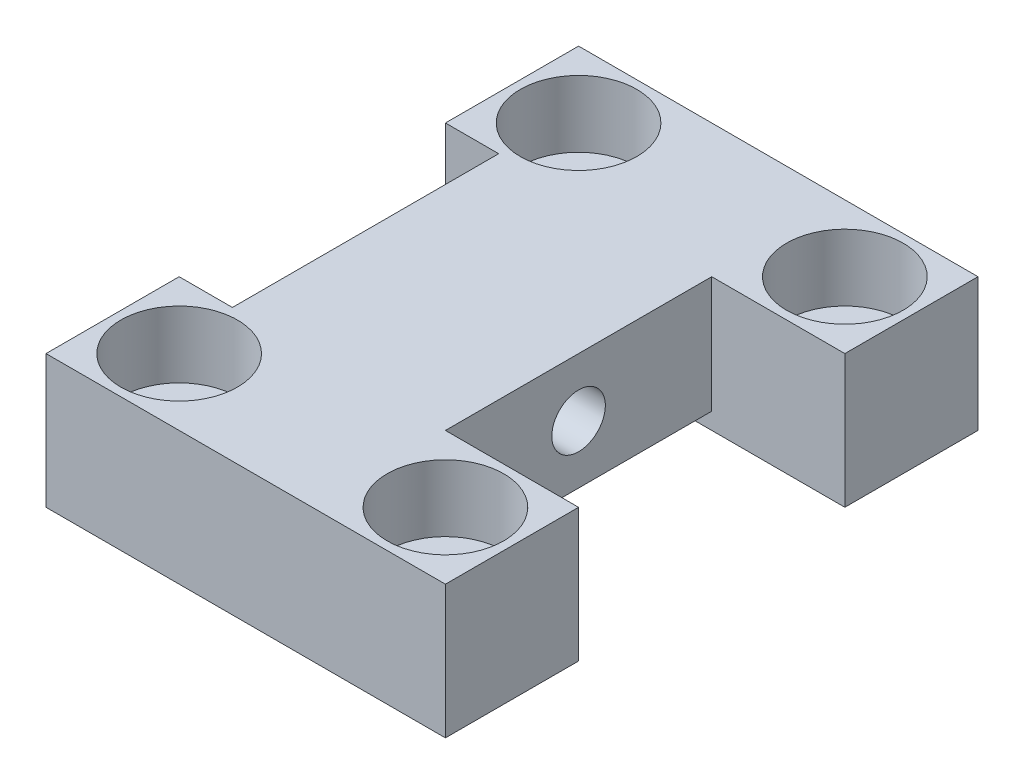
SolidWorks part; units mm, degrees
ref_plane "Front Plane" through (0, 0, 0) normal (0, 0, 1) x (1, 0, 0)
ref_plane "Top Plane" through (0, 0, 0) normal (0, 1, 0) x (1, 0, 0)
ref_plane "Right Plane" through (0, 0, 0) normal (1, 0, 0) x (0, 0, -1)
sketch "Sketch1" plane through (0, 0, 0) normal (0, 1, 0) x (1, 0, 0)
  line L0 (-19.05, 25.4) -> (19.05, -25.4) construction
  line L1 (-19.05, 25.4) -> (19.05, 25.4)
  line L2 (-19.05, 25.4) -> (-19.05, -25.4)
  line L3 (-19.05, -25.4) -> (19.05, -25.4)
  line L4 (19.05, 25.4) -> (19.05, -25.4)
  dimension "D1" = 50.8
  dimension "D2" = 38.1
extrude "Extrude1" add sketch "Sketch1" along normal blind 12.7
hole_wizard "CBORE for 1/4 Socket Head Cap Screw1" positions "Sketch10" profile "Sketch9" counterbore size "1/4" standard "Ansi Inch" end condition through all
sketch "Sketch10" plane through (0, 12.7, 0) normal (0, 1, 0) x (-1, 0, 0)
  line L1 (-12.7, -19.05) -> (12.7, -19.05)
  line L2 (-12.7, -19.05) -> (-12.7, 19.05)
  line L3 (-12.7, 19.05) -> (12.7, 19.05)
  line L4 (12.7, -19.05) -> (12.7, 19.05)
  line L5 (-12.7, -19.05) -> (12.7, 19.05) construction
  point P0 (12.7, -19.05)
  point P1 (-12.7, -19.05)
  point P3 (-12.7, 19.05)
  point P5 (12.7, 19.05)
  dimension "D1" = 25.4
  dimension "D2" = 38.1
sketch "Sketch9" plane through (-12.7, 12.7, -19.05) normal (1, 0, 0) x (0, 0, 1)
  line L0 (0, 0) -> (0, 12.7)
  line L1 (0, 12.7) -> (3.3782, 12.7)
  line L3 (3.3782, 12.7) -> (3.3782, 6.35)
  line L4 (3.3782, 6.35) -> (5.5562, 6.35)
  line L5 (5.5562, 6.35) -> (5.5562, 0)
  line L7 (5.5562, 0) -> (0, 0)
  line L11 (0, -6.35) -> (0, 107.95) construction
  dimension "Thru Hole Dia." = 6.7564
  dimension "Thru Hole Depth" = 12.7
  dimension "C'Bore Dia." = 11.1125
  dimension "C'Bore Depth" = 6.35
sketch "Sketch3" plane through (0, 12.7, 0) normal (0, 1, 0) x (-1, 0, 0)
  line L0 (19.05, -25.4) -> (19.05, 25.4) construction
  line L1 (19.05, -12.7) -> (13.97, -12.7)
  line L2 (19.05, -12.7) -> (19.05, 12.7)
  line L3 (19.05, 12.7) -> (13.97, 12.7)
  line L4 (13.97, -12.7) -> (13.97, 12.7)
  line L5 (-19.05, 25.4) -> (-19.05, -25.4) construction
  line L6 (-19.05, -12.7) -> (-6.35, -12.7)
  line L7 (-19.05, -12.7) -> (-19.05, 12.7)
  line L8 (-19.05, 12.7) -> (-6.35, 12.7)
  line L9 (-6.35, -12.7) -> (-6.35, 12.7)
  line L10 (19.05, 0) -> (-19.05, 0) construction
  line L11 (-19.05, -25.4) -> (19.05, -25.4) construction
  dimension "D1" = 12.7
  dimension "D2" = 5.08
  dimension "D3" = 12.7
extrude "Cut-Extrude2" cut sketch "Sketch3" against normal through all
sketch "Sketch5" plane through (0, 0, 0) normal (0, -1, 0) x (1, 0, 0)
  line L0 (-13.97, 12.7) -> (-13.97, -12.7) construction
  line L1 (-13.97, 12.7) -> (6.35, 12.7)
  line L2 (-13.97, 12.7) -> (-13.97, -12.7)
  line L3 (-13.97, -12.7) -> (6.35, -12.7)
  line L4 (6.35, 12.7) -> (6.35, -12.7)
  line L5 (6.35, -12.7) -> (6.35, 12.7) construction
  point P8 (-13.97, 0)
  dimension "D1" = 25.4
extrude "Cut-Extrude4" cut sketch "Sketch5" against normal blind 1.5875
hole_wizard "1/4-20 Tapped Hole1" positions "Sketch7" profile "Sketch6" tap size "1/4-20" standard "Ansi Inch" end condition through all
sketch "Sketch7" plane through (-13.97, 0, 0) normal (-1, 0, 0) x (0, 0, 1)
  line L0 (12.7, 12.7) -> (-12.7, 1.5875) construction
  point P0 (0, 7.1437)
sketch "Sketch6" plane through (-13.97, 7.1437, 0) normal (0, 1, 0) x (0, 0, 1)
  line L0 (0, 0) -> (0, 33.02)
  line L1 (0, 33.02) -> (2.5527, 33.02)
  line L2 (2.5527, 33.02) -> (2.5527, 0)
  line L5 (2.5527, 0) -> (0, 0)
  line L11 (0, -6.35) -> (0, 107.95) construction
  dimension "Thru Tap Drill Dia." = 5.1054
  dimension "Thru Tap Drill Depth" = 33.02
cosmetic thread "Hole Thread1" parameters "D2"=6.35
